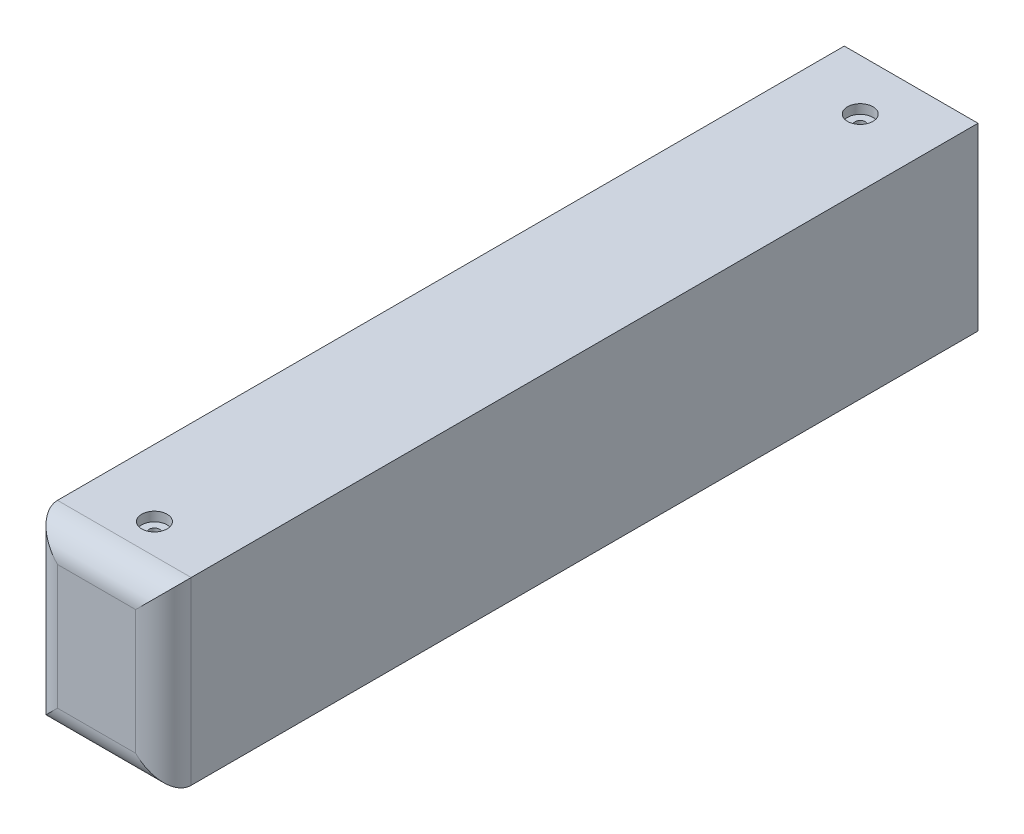
SolidWorks part; units mm, degrees
ref_plane "Ebene vorne" through (0, 0, 0) normal (0, 0, 1) x (1, 0, 0)
ref_plane "Ebene oben" through (0, 0, 0) normal (0, 1, 0) x (1, 0, 0)
ref_plane "Ebene rechts" through (0, 0, 0) normal (1, 0, 0) x (0, 0, -1)
sketch "Skizze1" plane through (0, 0, 0) normal (0, 0, 1) x (1, 0, 0)
  line L1 (57.7778, -77.7778) -> (-57.7778, -77.7778)
  line L2 (57.7778, -77.7778) -> (57.7778, 77.7778)
  line L3 (57.7778, 77.7778) -> (-57.7778, 77.7778)
  line L4 (-57.7778, -77.7778) -> (-57.7778, 77.7778)
  line L5 (57.7778, -77.7778) -> (-57.7778, 77.7778) construction
  line L6 (57.7778, 77.7778) -> (-57.7778, -77.7778) construction
  point P0 (0, 0)
  dimension "D1" = 155.5556
  dimension "D2" = 115.5556
extrude "Aufsatz-Linear austragen1" add sketch "Skizze1" along normal blind 704
sketch "Skizze2" plane through (57.7778, 0, 0) normal (1, 0, 0) x (0, 0, -1)
  line L0 (-704, -77.7778) -> (-704, 77.7778) construction
  line L1 (-704, 77.7778) -> (0, 77.7778) construction
  line L2 (-704, 53.7778) -> (-704, 77.7778)
  line L3 (-704, 77.7778) -> (-680, 77.7778)
  arc A0 (-680, 77.7778) -> (-704, 53.7778) centre (-680, 53.7778) ccw
  dimension "D1" = 48
extrude "Schnitt-Linear austragen1" cut sketch "Skizze2" against normal through all
sketch "Skizze3" plane through (0, 77.7778, 0) normal (0, 1, 0) x (1, 0, 0)
  line L0 (-57.7778, -680) -> (-57.7778, 0) construction
  line L1 (-57.7778, -704) -> (57.7778, -704) construction
  line L2 (-57.7778, -680) -> (-57.7778, -704)
  line L3 (-57.7778, -680) -> (-57.7778, -704) construction
  line L4 (-57.7778, -704) -> (-33.7778, -704)
  arc A0 (-57.7778, -680) -> (-33.7778, -704) centre (-33.7778, -680) ccw
  dimension "D1" = 48
extrude "Schnitt-Linear austragen2" cut sketch "Skizze3" against normal through all contours L4 A0 L2
mirror "Spiegeln1" about plane through (0, 0, 0) normal (0, 1, 0) of "Schnitt-Linear austragen1"
mirror "Spiegeln2" about plane through (0, 0, 0) normal (1, 0, 0) of "Schnitt-Linear austragen2", "Spiegeln1"
hole_wizard "Stirnsenkung für M8 Senkschraube (Kopf Button)1" positions "Skizze5" profile "Skizze4" counterbore size "M8" standard "ANSI Metrisch" end condition through all
sketch "Skizze5" plane through (0, 77.7778, 0) normal (0, 1, 0) x (1, 0, 0)
  line L1 (-33.7778, -704) -> (33.7778, -704) construction
  point P0 (0, -654)
  point P8 (0, -44)
  point P10 (0, -44)
  dimension "D1" = 50
  dimension "D2" = 610
sketch "Skizze4" plane through (0, 77.7778, 654) normal (1, 0, 0) x (0, 0, 1)
  line L0 (0, 0) -> (0, 155.5556)
  line L1 (0, 155.5556) -> (4.5, 155.5556)
  line L3 (4.5, 155.5556) -> (4.5, 8)
  line L4 (4.5, 8) -> (11, 8)
  line L5 (11, 8) -> (11, 0)
  line L7 (11, 0) -> (0, 0)
  line L11 (0, -6.35) -> (0, 107.95) construction
  dimension "Bohrerdurchmesser" = 9
  dimension "Bohrungstiefe" = 155.5556
  dimension "Senkdurchmesser2" = 22
  dimension "Senktiefe2" = 8
hole_wizard "Stirnsenkung für M8 Senkschraube (Kopf Button)2" positions "Skizze7" profile "Skizze6" counterbore size "M8" standard "ANSI Metrisch" end condition through all
sketch "Skizze7" plane through (0, -77.7778, 0) normal (0, -1, 0) x (-1, 0, 0)
  point P7 (0, -654)
  point P14 (0, -44)
sketch "Skizze6" plane through (0, -77.7778, 654) normal (1, 0, 0) x (0, 0, -1)
  line L0 (0, 0) -> (0, 155.5556)
  line L1 (0, 155.5556) -> (4.5, 155.5556)
  line L3 (4.5, 155.5556) -> (4.5, 8)
  line L4 (4.5, 8) -> (7.5, 8)
  line L5 (7.5, 8) -> (7.5, 0)
  line L7 (7.5, 0) -> (0, 0)
  line L11 (0, -6.35) -> (0, 107.95) construction
  dimension "Bohrerdurchmesser" = 9
  dimension "Bohrungstiefe" = 155.5556
  dimension "Senkdurchmesser2" = 15
  dimension "Senktiefe2" = 8
